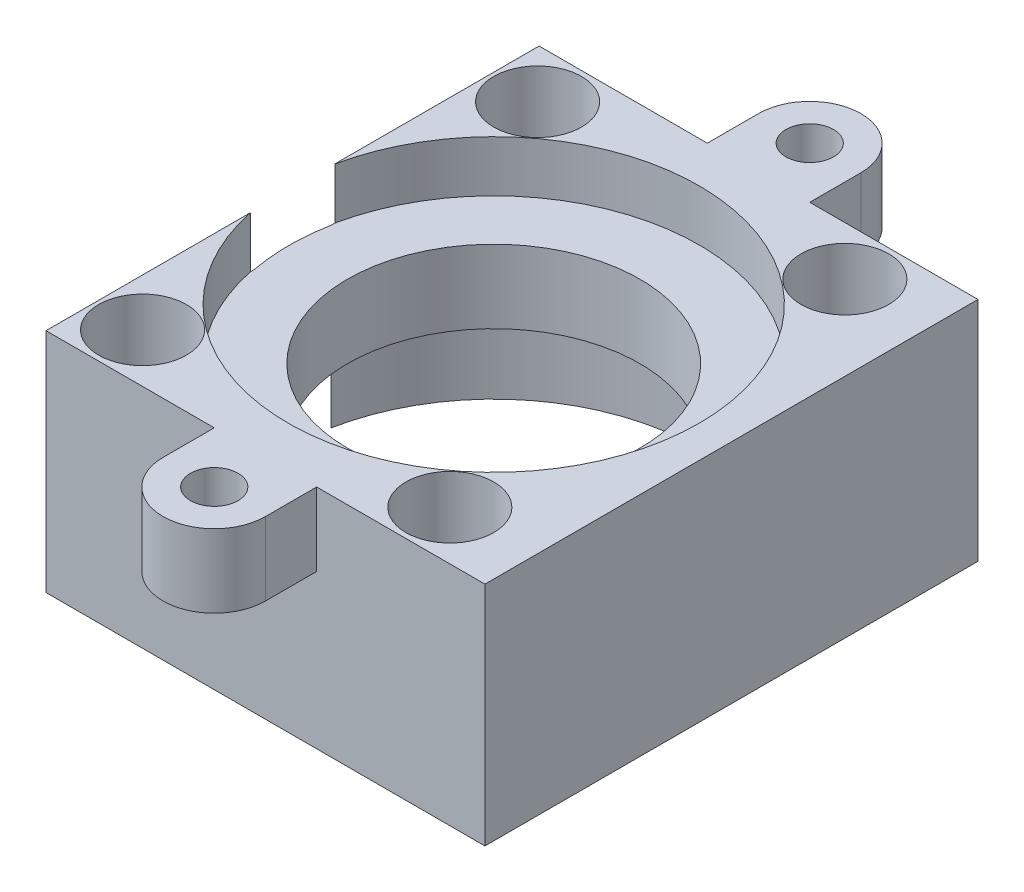
SolidWorks part; units mm, degrees
ref_plane "Front Plane" through (0, 0, 0) normal (0, 0, 1) x (1, 0, 0)
ref_plane "Top Plane" through (0, 0, 0) normal (0, 1, 0) x (1, 0, 0)
ref_plane "Right Plane" through (0, 0, 0) normal (1, 0, 0) x (0, 0, -1)
sketch "Sketch1" plane through (0, 0, 0) normal (0, 1, 0) x (1, 0, 0)
  line L1 (15, -16.85) -> (-15, -16.85)
  line L2 (15, -16.85) -> (15, 16.85)
  line L3 (15, 16.85) -> (-15, 16.85)
  line L4 (-15, -16.85) -> (-15, 16.85)
  line L5 (15, -16.85) -> (-15, 16.85) construction
  line L6 (15, 16.85) -> (-15, -16.85) construction
  circle A0 centre (-11.75, 13.5) radius 1.375
  circle A1 centre (-11.75, -13.5) radius 1.375
  circle A2 centre (9.25, -13.5) radius 1.4608
  circle A3 centre (9.25, 13.5) radius 1.4807
  circle A4 centre (-1.25, 0) radius 14
  point P0 (0, 0)
  dimension "D3" = 27
  dimension "D4" = 2.75
  dimension "D5" = 2.75
  dimension "D6" = 3.35
  dimension "D7" = 3.25
  dimension "D8" = 3.25
  dimension "D9" = 21
  dimension "D10" = 21
  dimension "D11" = 3.35
  dimension "D12" = 3.35
  dimension "D13" = 28
  dimension "D14" = 13.75
  dimension "D1" = 33.7
  dimension "D2" = 30
extrude "Boss-Extrude1" add sketch "Sketch1" along normal blind 15 contours A4 L4 L1 L2 L3 A3 A2 A1 A0
sketch "Sketch2" plane through (0, 15, 0) normal (0, 1, 0) x (1, 0, 0)
  circle A0 centre (-1.25, 0) radius 14
  circle A1 centre (-1.25, 0) radius 10
  dimension "D1" = 20
extrude "Boss-Extrude2" add sketch "Sketch2" against normal blind 8
sketch "Sketch3" plane through (0, 15, 0) normal (0, 1, 0) x (1, 0, 0)
  circle A0 centre (-1.25, 0) radius 14
  circle A1 centre (-1.25, 0) radius 10
extrude "Cut-Extrude1" cut sketch "Sketch3" against normal blind 3
sketch "Sketch5" plane through (0, 15, 0) normal (0, 1, 0) x (1, 0, 0)
  line L1 (15, -16.85) -> (-15, -16.85)
  line L2 (15, -16.85) -> (15, 16.85)
  line L3 (15, 16.85) -> (-15, 16.85)
  line L4 (-15, -16.85) -> (-15, 16.85)
  line L5 (15, -16.85) -> (-15, 16.85) construction
  line L6 (15, 16.85) -> (-15, -16.85) construction
  circle A0 centre (-1.25, 0) radius 14
  circle A1 centre (-11.75, 13.5) radius 1.375
  circle A2 centre (9.25, 13.5) radius 1.4807
  circle A3 centre (9.25, -13.5) radius 1.4608
  circle A4 centre (-11.75, -13.5) radius 1.375
  point P3 (0, 0)
  arc M1 (-15, 2.6339) -> (-15, -2.6339) centre (-1.25, 0) cw
  line M2 (-15, -2.6339) -> (-15, -16.85)
  line M3 (-15, -16.85) -> (15, -16.85)
  line M4 (15, -16.85) -> (15, 16.85)
  line M5 (15, 16.85) -> (-15, 16.85)
  line M6 (-15, 16.85) -> (-15, 2.6339)
  circle M7 centre (9.25, 13.5) radius 1.4807
  circle M8 centre (9.25, -13.5) radius 1.4608
  circle M9 centre (-11.75, -13.5) radius 1.375
  circle M10 centre (-11.75, 13.5) radius 1.375
extrude "Boss-Extrude3" add sketch "Sketch5" along normal blind 0.5 contours M6 M1 M2 M3 M4 M5 M7 M9 M10 M8
sketch "Sketch6" plane through (0, 15.5, 0) normal (0, 1, 0) x (1, 0, 0)
  line L0 (15, 16.85) -> (-15, 16.85) construction
  line L1 (-15, -16.85) -> (15, -16.85) construction
  line L3 (-3.5, 20.35) -> (3.5, 20.35)
  line L4 (-3.5, 20.35) -> (-3.5, -20.35)
  line L5 (-3.5, -20.35) -> (3.5, -20.35)
  line L6 (3.5, 20.35) -> (3.5, -20.35)
  circle A0 centre (0, 20.35) radius 1.625
  circle A1 centre (0, -20.35) radius 1.625
  circle A2 centre (0, 20.35) radius 3.5
  circle A3 centre (0, -20.35) radius 3.5
  line M8 (-15, -16.85) -> (15, -16.85)
  line M10 (15, 16.85) -> (-15, 16.85)
  dimension "D1" = 3.25
  dimension "D2" = 3.25
  dimension "D3" = 7
  dimension "D4" = 7
  dimension "D5" = 3.5
  dimension "D6" = 3.5
extrude "Boss-Extrude4" add sketch "Sketch6" against normal blind 5 contours L3 A2 A0 | A2 L3 A0 | A2 L6 M10 | A2 L4 M10 | A3 L4 M8 | A3 L6 M8 | L5 A3 A1 | L5 A3 A1
sketch "Sketch7" plane through (0, 15.5, 0) normal (0, 1, 0) x (1, 0, 0)
  circle A0 centre (-11.75, 13.5) radius 3
  circle A1 centre (9.25, 13.5) radius 3
  circle A2 centre (9.25, -13.5) radius 3
  circle A3 centre (-11.75, -13.5) radius 3
  dimension "D1" = 6
  dimension "D2" = 6
  dimension "D3" = 6
  dimension "D4" = 6
extrude "Cut-Extrude2" cut sketch "Sketch7" against normal blind 12.5
sketch "Sketch8" plane through (0, 15.5, 0) normal (0, 1, 0) x (1, 0, 0)
  circle A0 centre (-1.25, 0) radius 14.05
  dimension "D1" = 28.1
extrude "Cut-Extrude3" cut sketch "Sketch8" against normal blind 3.5
